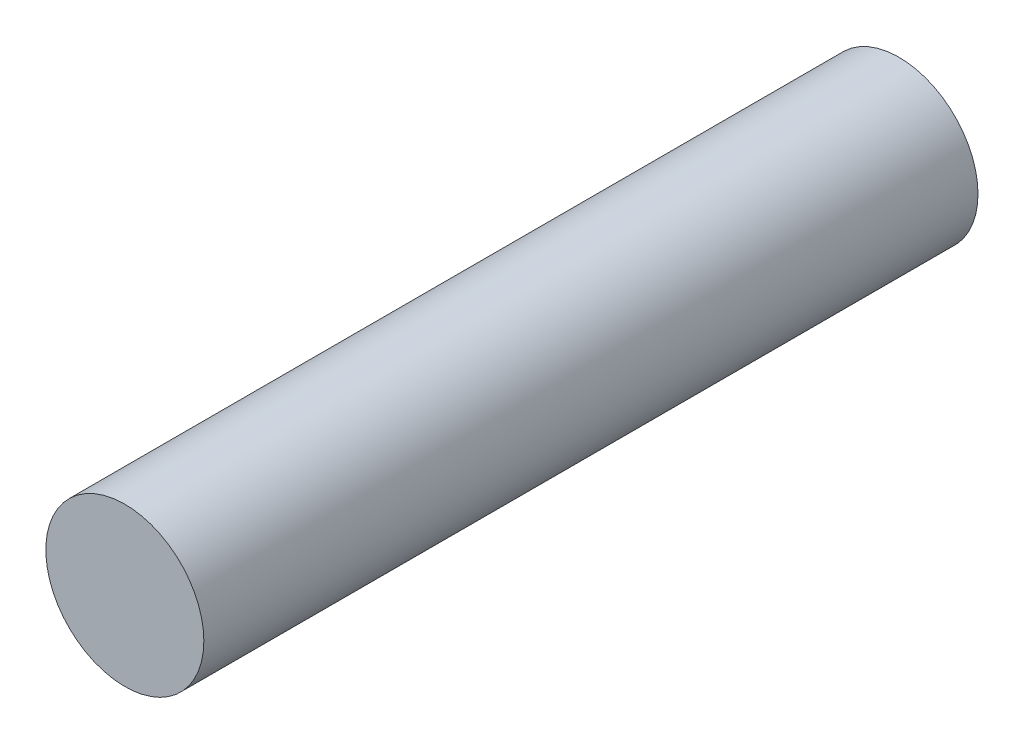
SolidWorks part; units mm, degrees
ref_plane "Plan de face" through (0, 0, 0) normal (0, 0, 1) x (1, 0, 0)
ref_plane "Plan de dessus" through (0, 0, 0) normal (0, 1, 0) x (1, 0, 0)
ref_plane "Plan de droite" through (0, 0, 0) normal (1, 0, 0) x (0, 0, -1)
sketch "Esquisse1" plane through (0, 0, 0) normal (0, 0, 1) x (1, 0, 0)
  circle A0 centre (0, 0) radius 5
  dimension "D1" = 10
extrude "Boss.-Extru.1" add sketch "Esquisse1" along normal blind 49
sketch "Esquisse2" plane through (0, 0, 49) normal (0, 0, 1) x (1, 0, 0)
  line L0 (-17.1922, 0) -> (18.7445, 0) construction
  line L1 (18.7445, 0) -> (0, 15.7369) construction
  line L2 (0, 15.7369) -> (0.7762, -16.5519) construction
  circle A0 centre (0.3783, 0) radius 2.5
  dimension "D1" = 5
